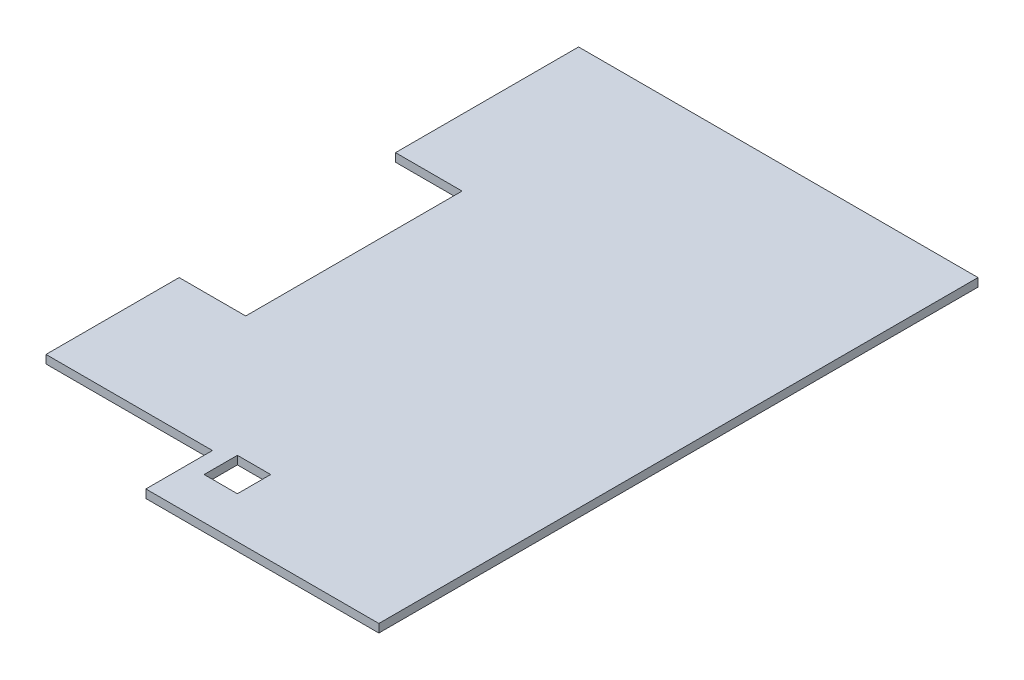
SolidWorks part; units mm, degrees
ref_plane "Front Plane" through (0, 0, 0) normal (0, 0, 1) x (1, 0, 0)
ref_plane "Top Plane" through (0, 0, 0) normal (0, 1, 0) x (1, 0, 0)
ref_plane "Right Plane" through (0, 0, 0) normal (1, 0, 0) x (0, 0, -1)
sketch "Sketch2" plane through (0, 0, 0) normal (0, 1, 0) x (1, 0, 0)
  line L0 (0, 0) -> (254, 0)
  line L1 (254, 0) -> (254, -101.6)
  line L2 (254, -101.6) -> (609.6, -101.6)
  line L3 (609.6, -101.6) -> (609.6, 812.8)
  line L4 (609.6, 812.8) -> (0, 812.8)
  line L5 (0, 812.8) -> (0, 533.4)
  line L6 (0, 533.4) -> (101.6, 533.4)
  line L7 (101.6, 533.4) -> (101.6, 203.2)
  line L8 (101.6, 203.2) -> (0, 203.2)
  line L9 (0, 203.2) -> (0, 0)
  dimension "D1" = 254
  dimension "D2" = 101.6
  dimension "D3" = 355.6
  dimension "D4" = 914.4
  dimension "D5" = 279.4
  dimension "D6" = 101.6
  dimension "D7" = 330.2
extrude "Boss-Extrude1" add sketch "Sketch2" along normal blind 12.7
sketch "Sketch3" plane through (0, 12.7, 0) normal (0, 1, 0) x (1, 0, 0)
  line L0 (254, 0) -> (254, 12.7)
  line L1 (254, 12.7) -> (279.4, 12.7)
  line L2 (279.4, 12.7) -> (279.4, -38.1)
  line L3 (279.4, -38.1) -> (330.2, -38.1)
  line L4 (330.2, -38.1) -> (330.2, 12.7)
  line L5 (330.2, 12.7) -> (279.4, 12.7)
  dimension "D1" = 25.4
  dimension "D2" = 12.7
  dimension "D3" = 50.8
  dimension "D4" = 50.8
extrude "Cut-Extrude1" cut sketch "Sketch3" against normal blind 12.7 contours L2 L3 L4 L5
